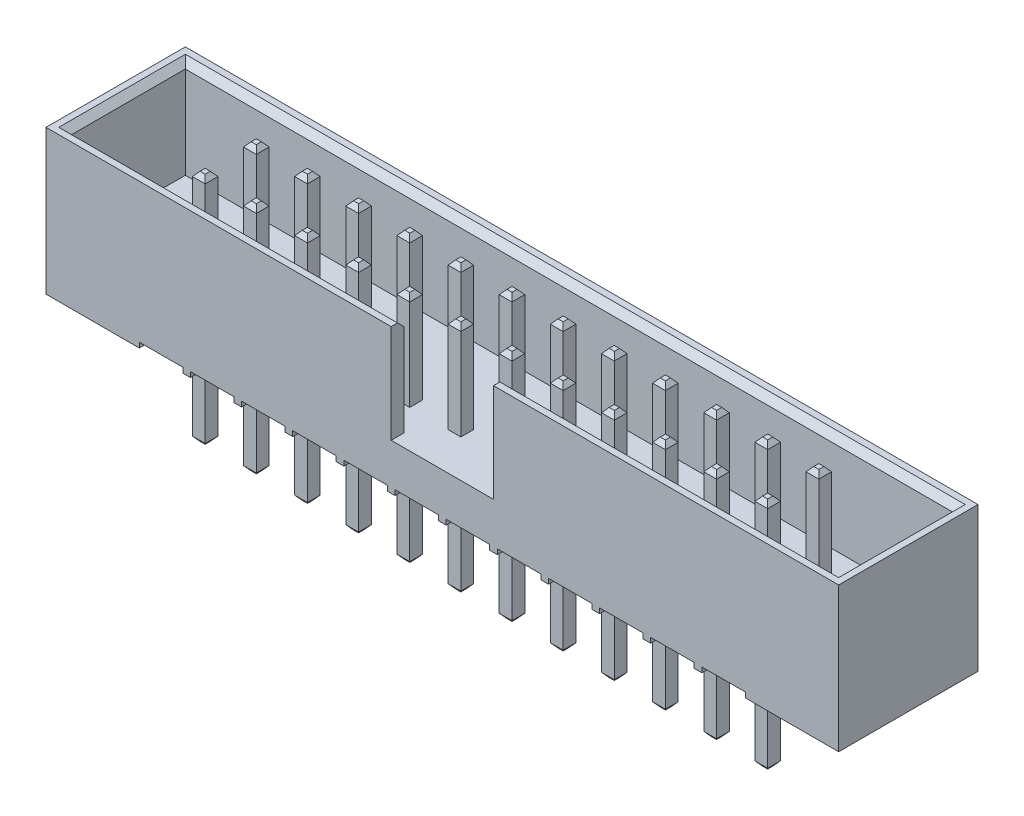
SolidWorks part; units mm, degrees
ref_plane "Спереди" through (0, 0, 0) normal (0, 0, 1) x (1, 0, 0)
ref_plane "Сверху" through (0, 0, 0) normal (0, 1, 0) x (1, 0, 0)
ref_plane "Справа" through (0, 0, 0) normal (1, 0, 0) x (0, 0, -1)
ref_plane "Плоскость1" through (0, -3.6, 0) normal (0, 1, 0) x (1, 0, 0)
sketch "Эскиз1" plane through (0, 0, 0) normal (0, 1, 0) x (1, 0, 0)
  line L1 (0, 0) -> (31, 0)
  line L2 (0, 0) -> (0, 5.45)
  line L3 (0, 5.45) -> (31, 5.45)
  line L4 (31, 0) -> (31, 5.45)
  dimension "D1" = 5.45
  dimension "A" = 31
extrude "Корпус" add sketch "Эскиз1" along normal blind 5.65
sketch "Эскиз6" plane through (0, 0, 0) normal (0, 0, 1) x (1, 0, 0)
  line L0 (0, 5.65) -> (0, 0) construction
  line L1 (3.65, 0) -> (5.35, 0)
  line L2 (3.65, 0) -> (3.65, 0.2)
  line L3 (3.65, 0.2) -> (5.35, 0.2)
  line L4 (5.35, 0) -> (5.35, 0.2)
  line L5 (3.65, 0) -> (5.35, 0.2) construction
  line L6 (3.65, 0.2) -> (5.35, 0) construction
  line L7 (0, 0) -> (31, 0) construction
  point P0 (4.5, 0.1)
  dimension "D1" = 1.7
  dimension "D2" = 4.5
  dimension "D3" = 0.2
extrude "Вырез-Вытянуть7" cut sketch "Эскиз6" against normal through all
pattern_linear "Линейный массив3" count 12 spacing 2 along (1, 0, 0) of "Вырез-Вытянуть7"
sketch "Эскиз2" plane through (0, 5.65, 0) normal (0, 1, 0) x (1, 0, 0)
  line L0 (0, 5.45) -> (0, 0) construction
  line L1 (0.5, 0.5) -> (30.5, 0.5)
  line L2 (0.5, 0.5) -> (0.5, 4.95)
  line L3 (0.5, 4.95) -> (30.5, 4.95)
  line L4 (31, 5.45) -> (0, 5.45) construction
  line L7 (0, 0) -> (31, 0) construction
  line L8 (31, 0) -> (31, 5.45) construction
  line L12 (30.5, 0.5) -> (30.5, 4.95)
  dimension "D2" = 0.5
  dimension "D3" = 0.5
  dimension "D4" = 0.5
  dimension "D1" = 0.5
extrude "Вырез-Вытянуть2" cut sketch "Эскиз2" against normal offset from surface (3.85 mm away) 1.8 up to face at (29.175, 0, -2.725)
sketch "Эскиз3" plane through (0, 0, 0) normal (0, 0, 1) x (1, 0, 0)
  line L0 (0, 5.65) -> (31, 5.65) construction
  line L1 (13.5, 1.8) -> (17.5, 1.8)
  line L2 (13.5, 1.8) -> (13.5, 5.65)
  line L3 (13.5, 5.65) -> (17.5, 5.65)
  line L4 (17.5, 1.8) -> (17.5, 5.65)
  line L5 (13.5, 1.8) -> (17.5, 5.65) construction
  line L6 (13.5, 5.65) -> (17.5, 1.8) construction
  line L9 (15.5, 5.65) -> (15.5, 1.8) construction
  line L10 (0, 5.65) -> (0, 0) construction
  line L11 (31, 5.65) -> (31, 0) construction
  line L12 (0.5, 1.8) -> (30.5, 1.8) construction
  point P0 (15.5, 3.725)
  dimension "D1" = 4
extrude "Вырез-Вытянуть3" cut sketch "Эскиз3" against normal up to next
sketch "Эскиз5" plane through (0, -3.6, 0) normal (0, 1, 0) x (1, 0, 0)
  line L0 (4.25, 1.975) -> (4.5, 1.725) construction
  line L1 (4.25, 3.975) -> (4.5, 3.725) construction
  line L2 (4.5, 3.725) -> (4.75, 3.475) construction
  line L3 (4.5, 1.725) -> (4.75, 1.475) construction
  line L6 (0, 0) -> (13.5, 0) construction
  line L9 (4.25, 1.975) -> (4.75, 1.975)
  line L10 (4.25, 1.975) -> (4.25, 1.475)
  line L11 (4.25, 1.475) -> (4.75, 1.475)
  line L12 (4.75, 1.975) -> (4.75, 1.475)
  line L14 (4.25, 1.475) -> (4.75, 1.975) construction
  line L15 (4.25, 3.975) -> (4.75, 3.975)
  line L16 (4.25, 3.975) -> (4.25, 3.475)
  line L17 (4.25, 3.475) -> (4.75, 3.475)
  line L18 (4.75, 3.975) -> (4.75, 3.475)
  line L20 (4.25, 3.475) -> (4.75, 3.975) construction
  line L24 (0, 5.45) -> (0, 0) construction
  point P0 (4.5, 1.725)
  dimension "D1" = 0.5
  dimension "D2" = 2
  dimension "D3" = 4.5
  dimension "D4" = 1.725
extrude "Контакты" add sketch "Эскиз5" along normal offset from surface (9.15 mm away) 0.1 up to face at (15.5, 5.65, -1.9)
chamfer "Фаска (корпус)" distance 0.25 angle 45 5 edges at (24, 5.65, -0.5) (30.5, 5.65, -2.725) (7, 5.65, -0.5) (0.5, 5.65, -2.725) (15.5, 5.65, -4.95)
chamfer "Фаска (контакты)" distance 0.15 angle 50 16 edges at (4.5, -3.6, -3.975) (4.25, -3.6, -3.725) (4.5, -3.6, -3.475) (4.75, -3.6, -3.725) (4.5, -3.6, -1.975) (4.25, -3.6, -1.725) (4.5, -3.6, -1.475) (4.75, -3.6, -1.725) (4.75, 5.55, -3.725) (4.5, 5.55, -3.475) (4.25, 5.55, -3.725) (4.5, 5.55, -3.975) (4.75, 5.55, -1.725) (4.5, 5.55, -1.475) (4.25, 5.55, -1.725) (4.5, 5.55, -1.975)
pattern_linear "Линейный массив2" count 12 spacing 2 along (1, 0, 0) of "Контакты", "Фаска (контакты)"
